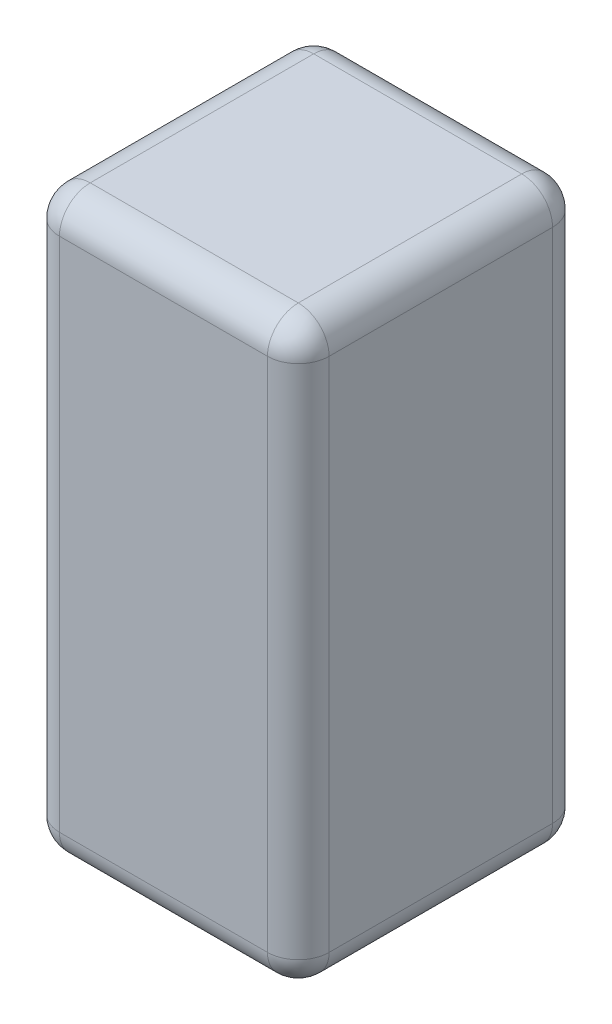
SolidWorks part; units mm, degrees
ref_plane "Front Plane" through (0, 0, 0) normal (0, 0, 1) x (1, 0, 0)
ref_plane "Top Plane" through (0, 0, 0) normal (0, 1, 0) x (1, 0, 0)
ref_plane "Right Plane" through (0, 0, 0) normal (1, 0, 0) x (0, 0, -1)
sketch "Sketch2" plane through (0, 0, 4) normal (0, 0, 1) x (1, 0, 0)
  line L0 (0, 0) -> (28.6597, 0) construction
  line L1 (17.5, 37.5) -> (-17.5, 37.5)
  line L2 (17.5, 37.5) -> (17.5, -37.5)
  line L3 (17.5, -37.5) -> (-17.5, -37.5)
  line L4 (-17.5, 37.5) -> (-17.5, -37.5)
  line L5 (0, 0) -> (0, 59.8919) construction
  dimension "D1" = 35
  dimension "D2" = 75
  dimension "D3" = 17.5
  dimension "D4" = 37.5
extrude "Boss-Extrude1" add sketch "Sketch2" along normal blind 37
fillet "Fillet1" radius 4 12 edges at (17.5, 0, 4) (17.5, 0, 41) (0, -37.5, 41) (0, -37.5, 4) (-17.5, 0, 4) (-17.5, 0, 41) (0, 37.5, 41) (0, 37.5, 4) (17.5, 37.5, 22.5) (-17.5, 37.5, 22.5) (17.5, -37.5, 22.5) (-17.5, -37.5, 22.5)
